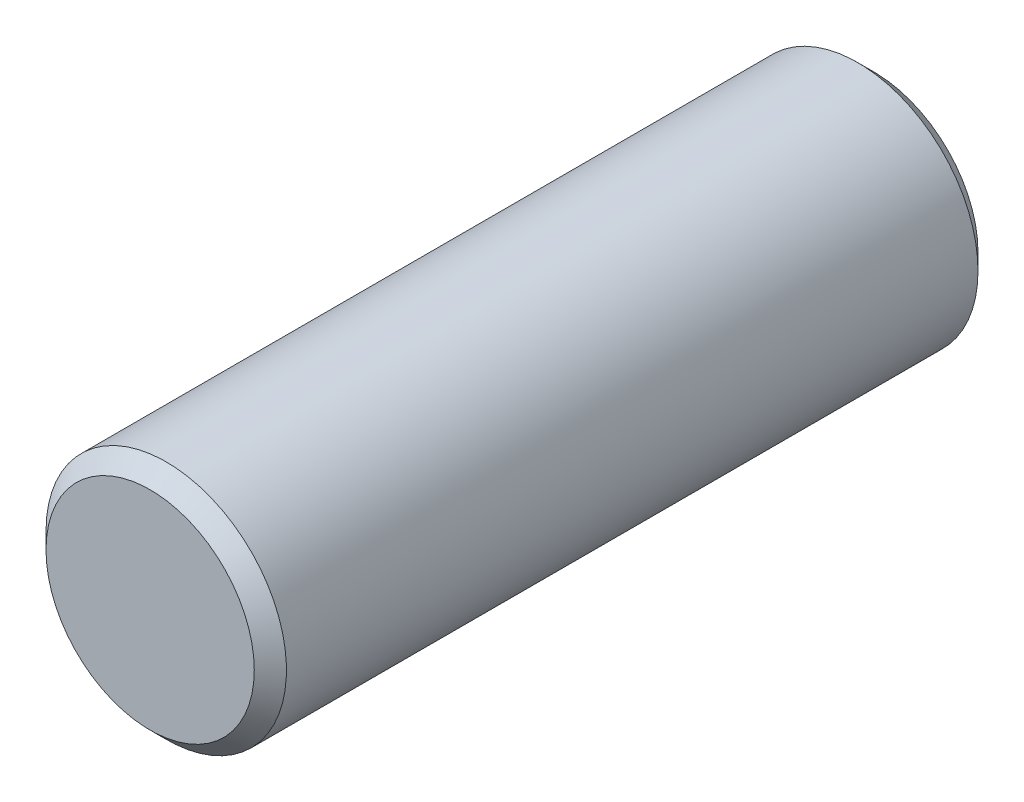
SolidWorks part; units mm, degrees
ref_plane "정면" through (0, 0, 0) normal (0, 0, 1) x (1, 0, 0)
ref_plane "윗면" through (0, 0, 0) normal (0, 1, 0) x (1, 0, 0)
ref_plane "우측면" through (0, 0, 0) normal (1, 0, 0) x (0, 0, -1)
sketch "스케치1" plane through (0, 0, 0) normal (0, 0, 1) x (1, 0, 0)
  circle A0 centre (0, 0) radius 7.475
  dimension "D1" = 14.95
extrude "보스-돌출1" add sketch "스케치1" along normal blind 45
chamfer "모따기1" distance 1 angle 45 2 edges at (7.475, 0, 45) (7.475, 0, 0)
